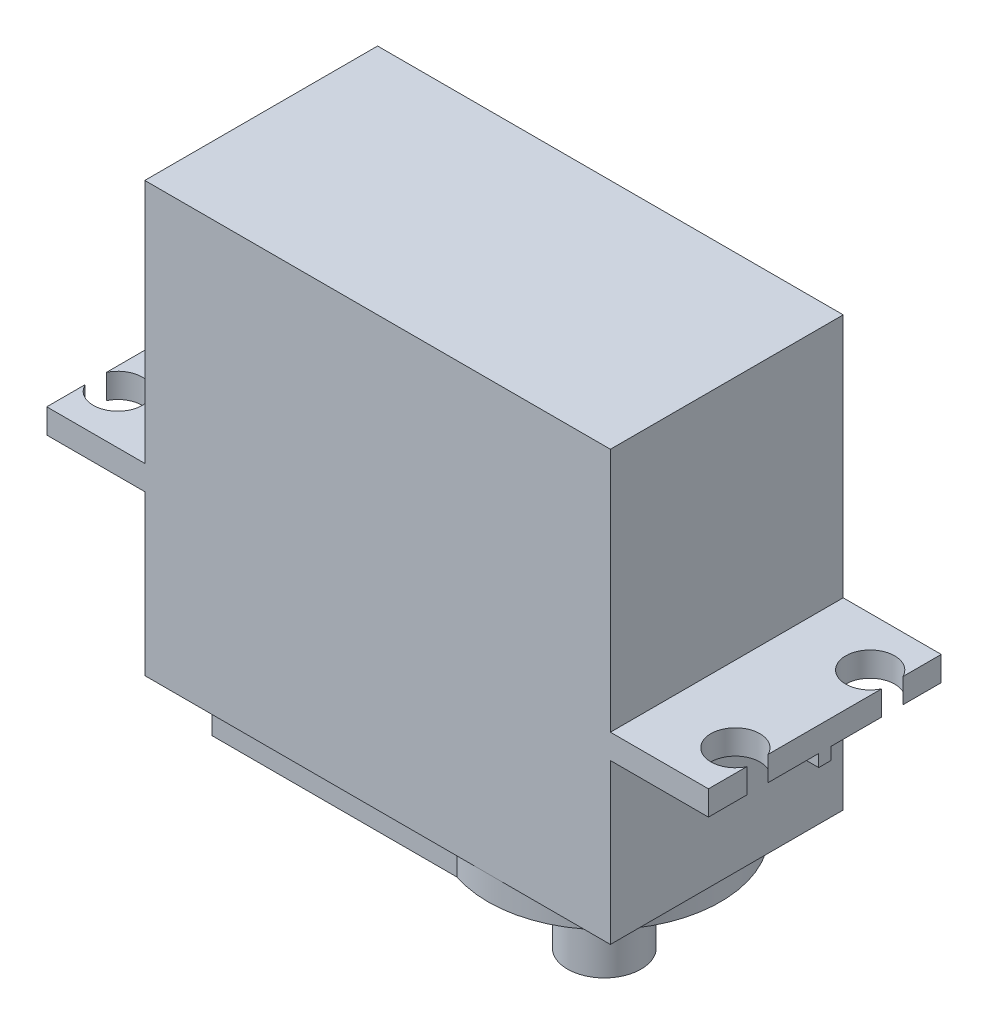
SolidWorks part; units mm, degrees
ref_plane "Front Plane" through (0, 0, 0) normal (0, 0, 1) x (1, 0, 0)
ref_plane "Top Plane" through (0, 0, 0) normal (0, 1, 0) x (1, 0, 0)
ref_plane "Right Plane" through (0, 0, 0) normal (1, 0, 0) x (0, 0, -1)
sketch "Sketch1" plane through (0, 0, 0) normal (0, 0, 1) x (1, 0, 0)
  line L0 (0, 0) -> (0, 37.699) construction
  line L1 (0, 0) -> (48.4915, 0) construction
  line L2 (19, 0) -> (-19, 0)
  line L3 (-19, 0) -> (-19, 13)
  line L4 (-19, 13) -> (-27, 13)
  line L5 (-27, 13) -> (-27, 15)
  line L6 (-27, 15) -> (-19, 15)
  line L7 (-19, 15) -> (-19, 35)
  line L8 (-19, 35) -> (19, 35)
  line L9 (19, 15) -> (19, 35)
  line L10 (27, 15) -> (19, 15)
  line L11 (27, 13) -> (27, 15)
  line L12 (19, 13) -> (27, 13)
  line L13 (19, 0) -> (19, 13)
  point P13 (0, 35)
  dimension "D1" = 19
  dimension "D2" = 13
  dimension "D3" = 2
  dimension "D4" = 35
  dimension "D5" = 8
extrude "Boss-Extrude1" add sketch "Sketch1" along normal blind 19
sketch "Sketch6" plane through (0, 15, 0) normal (0, 1, 0) x (1, 0, 0)
  line L0 (27, -19) -> (27, 0) construction
  line L1 (27, -19) -> (19, -19) construction
  line L2 (19, -9.5) -> (33.7393, -9.5) construction
  line L3 (19, -19) -> (19, 0) construction
  line L4 (0, -19.495) -> (0, 7.5047) construction
  circle A0 centre (25.2, -15) radius 2
  circle A1 centre (25.2, -4) radius 2
  circle A2 centre (-25.2, -4) radius 2
  circle A3 centre (-25.2, -15) radius 2
  dimension "D1" = 4
  dimension "D2" = 1.8
  dimension "D3" = 4
extrude "Cut-Extrude2" cut sketch "Sketch6" against normal through all
sketch "Sketch10" plane through (0, 13, 0) normal (0, -1, 0) x (1, 0, 0)
  line L0 (-19, 9.5) -> (-33.0939, 9.5) construction
  line L1 (-19, 19) -> (-19, 0) construction
  line L2 (-19, 10) -> (-19, 9)
  line L3 (-19, 19) -> (-19, 0) construction
  line L4 (-19, 9) -> (-27, 9)
  line L5 (-27, 14.1282) -> (-27, 4.8718) construction
  line L6 (-27, 9) -> (-27, 10)
  line L7 (-19, 10) -> (-27, 10)
  line L8 (0, 0) -> (0, 26.7518) construction
  line L9 (19, 9.5) -> (33.0939, 9.5) construction
  line L10 (19, 10) -> (27, 10)
  line L11 (27, 9) -> (27, 10)
  line L12 (19, 9) -> (27, 9)
  line L13 (19, 10) -> (19, 9)
  point P12 (-27, 9.5)
  point P22 (27, 9.5)
  dimension "D1" = 0.5
extrude "Boss-Extrude14" add sketch "Sketch10" along normal blind 1
sketch "Sketch12" plane through (0, 0, 0) normal (0, -1, 0) x (1, 0, 0)
  line L0 (-19, 19) -> (-19, 0) construction
  line L1 (-14, 18.5) -> (6, 18.5)
  line L2 (-14, 18.5) -> (-14, 0.5)
  line L3 (-14, 0.5) -> (6, 0.5)
  line L4 (19, 19) -> (19, 10) construction
  line L5 (-19, 19) -> (19, 19) construction
  line L6 (-19, 0) -> (19, 0) construction
  arc A0 (6, 18.5) -> (6, 0.5) centre (9, 9.5) cw
  dimension "D5" = 20
  dimension "D4" = 10
  dimension "D1" = 5
  dimension "D2" = 0.5
  dimension "D3" = 0.5
extrude "Boss-Extrude15" add sketch "Sketch12" along normal blind 2
sketch "Sketch13" plane through (0, -2, 0) normal (0, -1, 0) x (1, 0, 0)
  circle A0 centre (9, 9.5) radius 3
  dimension "D1" = 6
extrude "Cut-Extrude3" cut sketch "Sketch13" against normal blind 5
sketch "Sketch15" plane through (0, -2, 0) normal (0, -1, 0) x (1, 0, 0)
  circle A0 centre (9, 9.5) radius 3 construction
  circle A1 centre (9, 9.5) radius 3
extrude "Boss-Extrude16" add sketch "Sketch15" along normal blind 8
